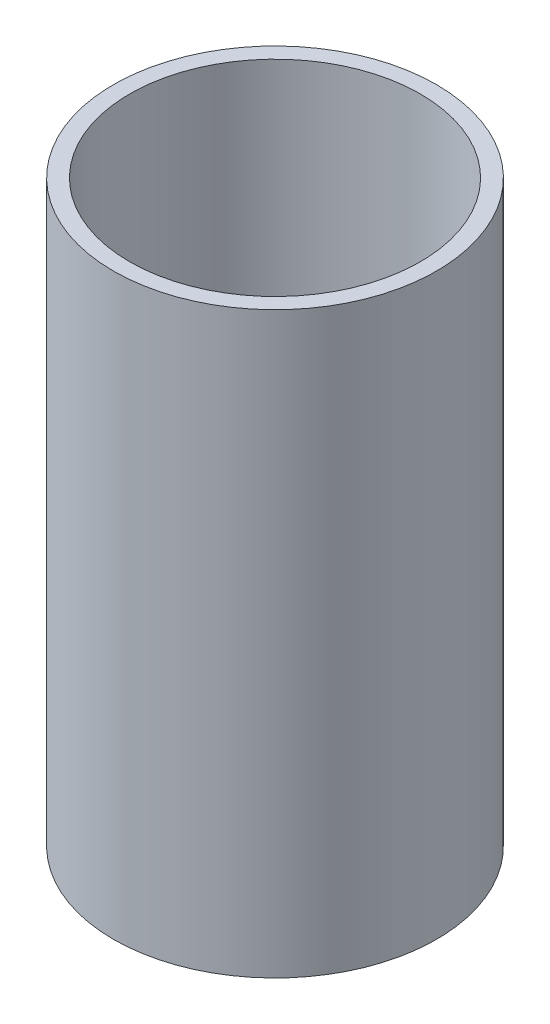
SolidWorks part; units mm, degrees
ref_plane "Front Plane" through (0, 0, 0) normal (0, 0, 1) x (1, 0, 0)
ref_plane "Top Plane" through (0, 0, 0) normal (0, 1, 0) x (1, 0, 0)
ref_plane "Right Plane" through (0, 0, 0) normal (1, 0, 0) x (0, 0, -1)
sketch "Sketch1" plane through (0, 0, 0) normal (0, 1, 0) x (1, 0, 0)
  circle A0 centre (0, 0) radius 20
  circle A1 centre (0, 0) radius 36
  circle A2 centre (0, 0) radius 40
  dimension "D1" = 40
  dimension "D2" = 72
  dimension "D3" = 80
extrude "Boss-Extrude1" add sketch "Sketch1" along normal blind 10
sketch "Sketch2" plane through (0, 0, 0) normal (0, 0, 1) x (1, 0, 0)
  line L0 (0, 85.4193) -> (0, -73.7814) construction
sketch "Sketch3" plane through (0, 0, 0) normal (1, 0, 0) x (0, 0, -1)
  line L0 (-40, 0) -> (40, 0) construction
  line L1 (-36, 10) -> (-20, 10) construction
  line L2 (-36, 10) -> (-36, 0) construction
  line L3 (-36, 0) -> (-20, 0) construction
  line L4 (-20, 10) -> (-20, 0) construction
  line L5 (20, 10) -> (-20, 10) construction
  line L6 (-20, 10) -> (-20, 0) construction
sketch "Sketch4" plane through (0, 0, 0) normal (1, 0, 0) x (0, 0, -1)
  line L0 (-4.2624, 0) -> (4.0314, 10)
  line L1 (-40, 0) -> (40, 0) construction
  line L2 (40, 10) -> (-40, 10) construction
  line L3 (-2.9787, 0) -> (5.3151, 10)
  line L4 (5.3151, 10) -> (4.0314, 10)
  line L5 (-4.2624, 0) -> (-2.9787, 0)
extrude "Boss-Extrude2" add sketch "Sketch4" against normal up to next and the other way up to next from offset 30
pattern_circular "CirPattern1" count 12 over 360 about axis through (0, 0, 0) along (0, 1, 0) of "Boss-Extrude2"
sketch "Sketch5" plane through (0, 10, 0) normal (0, 1, 0) x (1, 0, 0)
  circle A0 centre (0, 0) radius 3.1677
  dimension "D1" = 6.3355
extrude "Boss-Extrude3" add sketch "Sketch5" along normal blind 10
scale "Scale1" scale about origin uniform scaling yes scale factor 0.75
sketch "Sketch6" plane through (0, 7.5, 0) normal (0, 1, 0) x (1, 0, 0)
  circle A0 centre (0, 0) radius 30
  circle A1 centre (0, 0) radius 27
extrude "Boss-Extrude4" add sketch "Sketch6" along normal blind 100
equation "\"D1@Sketch1\"= \"D3@Sketch1\" / 2"
